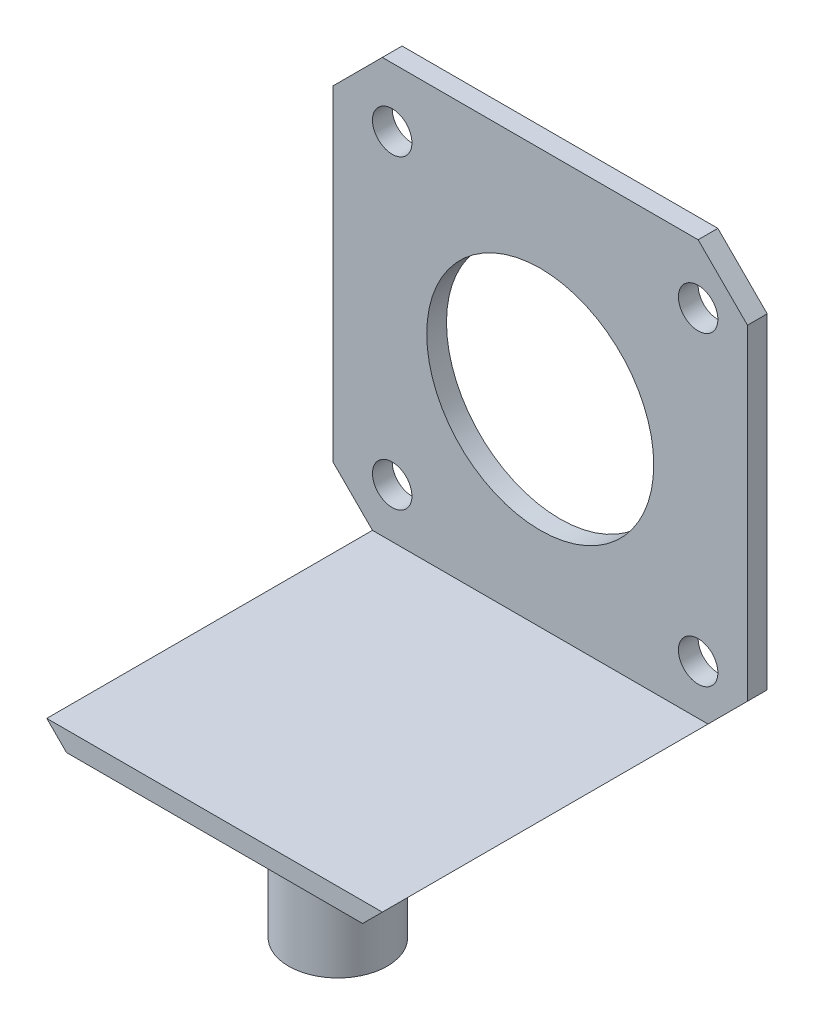
SolidWorks part; units mm, degrees
ref_plane "Front Plane" through (0, 0, 0) normal (0, 0, 1) x (1, 0, 0)
ref_plane "Top Plane" through (0, 0, 0) normal (0, 1, 0) x (1, 0, 0)
ref_plane "Right Plane" through (0, 0, 0) normal (1, 0, 0) x (0, 0, -1)
sketch "Sketch1" plane through (0, 0, 0) normal (0, 1, 0) x (1, 0, 0)
  circle A0 centre (0, 0) radius 5
  dimension "D1" = 10
extrude "Boss-Extrude1" add sketch "Sketch1" along normal blind 15
sketch "Sketch2" plane through (0, 15, 0) normal (0, 1, 0) x (1, 0, 0)
  line L0 (-2.2815, 1.5354) -> (-2.2815, -1.5354)
  arc A0 (-2.2815, -1.5354) -> (-2.2815, 1.5354) centre (0, 0) ccw
  dimension "D1" = 5.5
extrude "Cut-Extrude1" cut sketch "Sketch2" against normal through all
sketch "Sketch3" plane through (0, 15, 0) normal (0, 1, 0) x (1, 0, 0)
  line L1 (-21, -22.5) -> (21, -22.5)
  line L2 (-21, -22.5) -> (-21, 22.5)
  line L3 (-21, 22.5) -> (21, 22.5)
  line L4 (21, -22.5) -> (21, 22.5)
  line L5 (-21, -22.5) -> (21, 22.5) construction
  line L6 (-21, 22.5) -> (21, -22.5) construction
  point P0 (0, 0)
  dimension "D1" = 45
  dimension "D2" = 42
extrude "Boss-Extrude2" add sketch "Sketch3" along normal blind 2
sketch "Sketch4" plane through (0, 17, 0) normal (0, 1, 0) x (1, 0, 0)
  line L0 (21, -22.5) -> (21, 22.5) construction
  line L1 (-21, 22.5) -> (21, 22.5)
  line L2 (-21, 22.5) -> (-21, 20.5)
  line L3 (-21, 20.5) -> (21, 20.5)
  line L4 (21, 22.5) -> (21, 20.5)
  dimension "D1" = 2
extrude "Boss-Extrude3" add sketch "Sketch4" along normal blind 42
sketch "Sketch5" plane through (0, 0, -22.5) normal (0, 0, -1) x (-1, 0, 0)
  circle A0 centre (15, 53) radius 2
  circle A1 centre (-16, 53) radius 2
  circle A2 centre (15, 22) radius 2
  circle A3 centre (-16, 22) radius 2
  dimension "D1" = 4
  dimension "D2" = 4
  dimension "D3" = 4
  dimension "D4" = 4
sketch "Sketch6" plane through (0, 0, -22.5) normal (0, 0, -1) x (-1, 0, 0)
  line L0 (0, 59) -> (0, 15) construction
  line L1 (-21, 59) -> (21, 59) construction
  line L2 (-21, 15) -> (21, 15) construction
  line L3 (-21, 37) -> (21, 37) construction
  line L4 (-21, 59) -> (-21, 15) construction
  line L5 (21, 59) -> (21, 15) construction
  circle A0 centre (0, 37) radius 11.5
  dimension "D1" = 23
extrude "Cut-Extrude3" cut sketch "Sketch6" against normal blind 10
sketch "Sketch7" plane through (0, 17, 0) normal (0, 1, 0) x (1, 0, 0)
  line L0 (21, -22.5) -> (21, 20.5) construction
  line L1 (-21, -22.5) -> (21, -22.5)
  line L2 (-21, -22.5) -> (-21, -12.5)
  line L3 (-21, -12.5) -> (21, -12.5)
  line L4 (21, -22.5) -> (21, -12.5)
  dimension "D1" = 10
extrude "Cut-Extrude4" cut sketch "Sketch7" against normal blind 10
extrude "Cut-Extrude5" cut sketch "Sketch5" against normal blind 10
chamfer "Chamfer1" distance 5 angle 45 2 edges at (21, 59, -21.5) (-21, 59, -21.5)
chamfer "Chamfer2" distance 6 angle 45 2 edges at (21, 15, -5) (-21, 15, -5)
